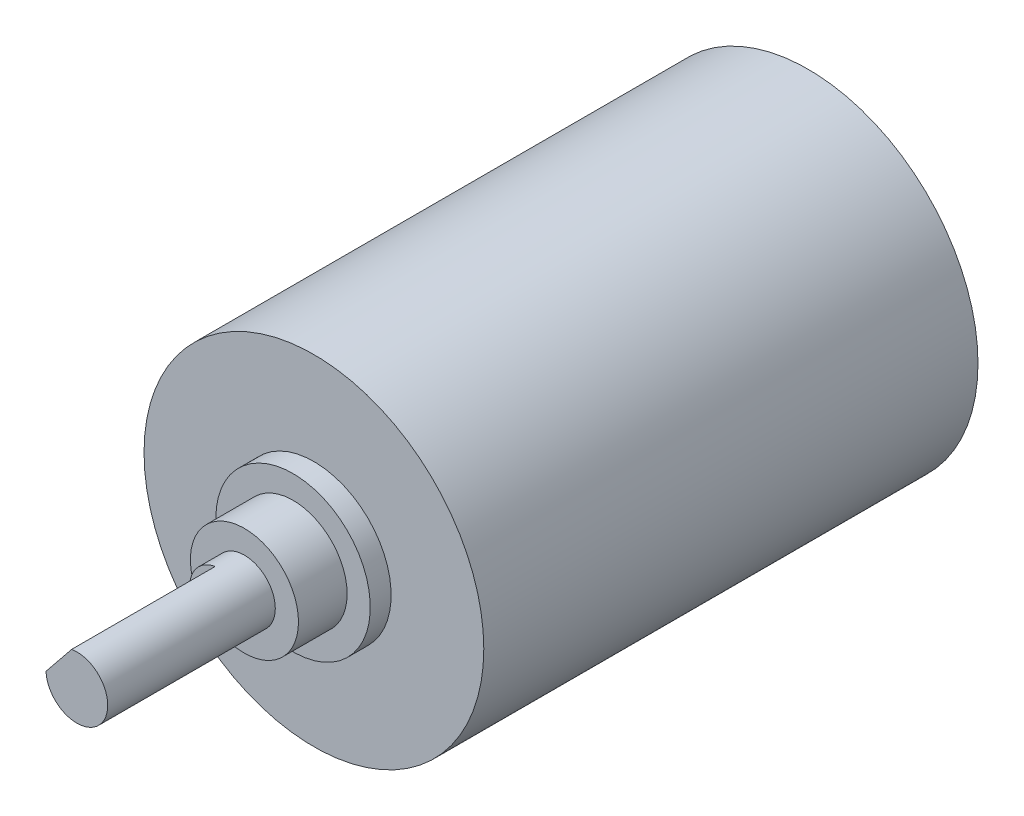
SolidWorks part; units mm, degrees
ref_plane "Front Plane" through (0, 0, 0) normal (0, 0, 1) x (1, 0, 0)
ref_plane "Top Plane" through (0, 0, 0) normal (0, 1, 0) x (1, 0, 0)
ref_plane "Right Plane" through (0, 0, 0) normal (1, 0, 0) x (0, 0, -1)
sketch "Sketch1" plane through (0, 0, 0) normal (0, 0, 1) x (1, 0, 0)
  circle A0 centre (0, 0) radius 11
extrude "Boss-Extrude1" add sketch "Sketch1" along normal blind 32 contours A0
sketch "Sketch2" plane through (0, 0, 32) normal (0, 0, 1) x (1, 0, 0)
  circle A0 centre (0, 0) radius 5
  dimension "D1" = 10
extrude "Boss-Extrude2" add sketch "Sketch2" along normal blind 1.35
sketch "Sketch3" plane through (0, 0, 33.35) normal (0, 0, 1) x (1, 0, 0)
  circle A0 centre (0, 0) radius 3.5
  dimension "D1" = 7
extrude "Boss-Extrude4" add sketch "Sketch3" along normal blind 3.15 contours A0
sketch "Sketch4" plane through (0, 0, 36.5) normal (0, 0, 1) x (1, 0, 0)
  circle A0 centre (0, 0) radius 2
extrude "Boss-Extrude5" add sketch "Sketch4" along normal blind 10.85
sketch "Sketch5" plane through (0, 0, 47.35) normal (0, 0, 1) x (1, 0, 0)
  line L0 (-0.338, 1.9712) -> (-1.998, -0.089)
  circle A0 centre (0, 0) radius 2 construction
  arc A1 (-0.338, 1.9712) -> (-1.998, -0.089) centre (0, 0) ccw
  dimension "D1" = 1.5
extrude "Cut-Extrude1" cut sketch "Sketch5" against normal blind 9.3
